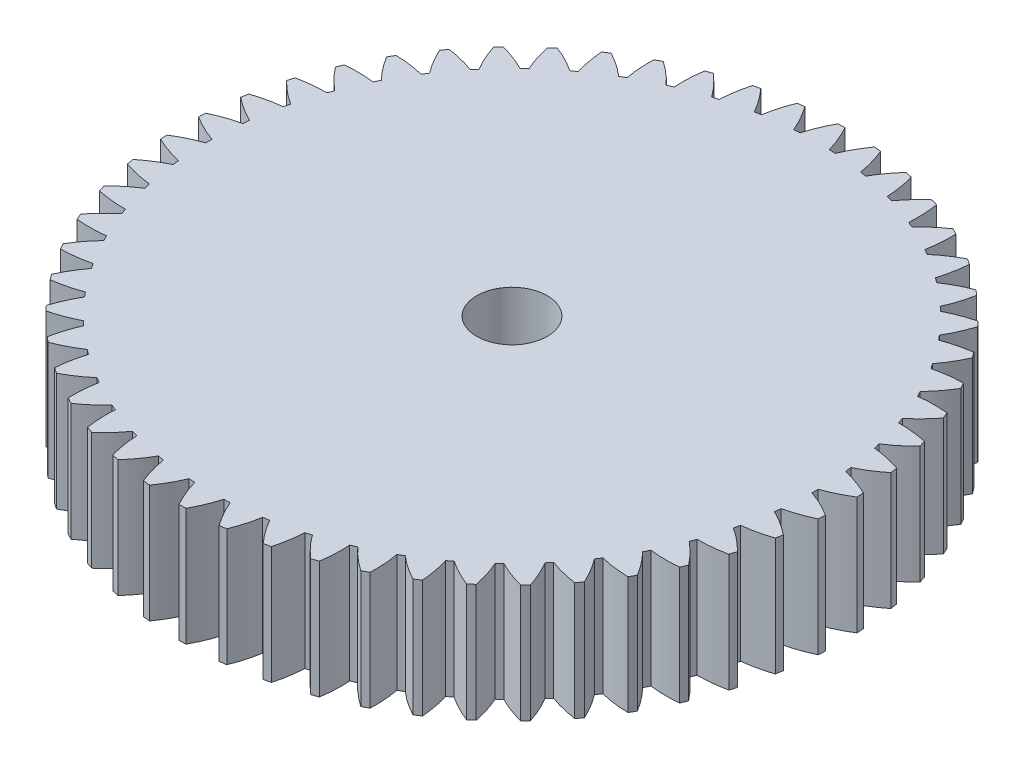
SolidWorks part; units mm, degrees
material "Custom Plastic"
ref_plane "Ön Düzlem" through (0, 0, 0) normal (0, 0, 1) x (1, 0, 0)
ref_plane "Üst Düzlem" through (0, 0, 0) normal (0, 1, 0) x (1, 0, 0)
ref_plane "Sağ Düzlem" through (0, 0, 0) normal (1, 0, 0) x (0, 0, -1)
sketch "Çizim2" plane through (0, 0, 0) normal (0, 1, 0) x (1, 0, 0)
  circle A0 centre (0, 0) radius 28
  dimension "D1" = 56
extrude "Yükseklik-Ekstrüzyon1" add sketch "Çizim2" along normal blind 10
sketch "Çizim3" plane through (0, 0, 0) normal (0, 1, 0) x (1, 0, 0)
  circle A0 centre (0, 0) radius 27
  circle A1 centre (0, 0) radius 28
  circle A2 centre (0, 0) radius 27
  circle A3 centre (0, 0) radius 28
  circle A4 centre (0, 0) radius 25.75
  circle A5 centre (0, 0) radius 24.47
  spline S0 degree 4 poles (24.4703, -0.0217) (24.4759, -0.0216) (24.4916, -0.0213) (24.5212, -0.0197) (24.5696, -0.0161) (24.6312, -0.0098) (24.7107, 0.0002) (24.8043, 0.0145) (24.907, 0.0329) (25.0185, 0.0556) (25.1296, 0.0808) (25.2402, 0.1082) (25.3502, 0.1376) (25.4832, 0.1756) (25.6424, 0.2247) (25.8278, 0.2869) (26.0374, 0.3633) (26.2501, 0.4475) (26.4588, 0.5354) (26.6686, 0.63) (26.8711, 0.7258) (27.0803, 0.8312) (27.2729, 0.9316) (27.4876, 1.0506) (27.6604, 1.1486) (27.887, 1.2848) (28.0205, 1.3674) (28.1762, 1.4664) (28.245, 1.5117) (28.2874, 1.5395) knots 0 0 0 0 0 0.005377 0.015084 0.028532 0.04661 0.064855 0.092111 0.119476 0.146842 0.174209 0.201575 0.228941 0.256307 0.307035 0.361767 0.4165 0.471232 0.525964 0.580697 0.635429 0.690161 0.744894 0.799626 0.854358 0.909091 0.954545 1 1 1 1 1 construction
  spline S1 degree 4 poles (24.4703, -0.0217) (24.4759, -0.0216) (24.4916, -0.0213) (24.5212, -0.0197) (24.5696, -0.0161) (24.6312, -0.0098) (24.7107, 0.0002) (24.8043, 0.0145) (24.907, 0.0329) (25.0185, 0.0556) (25.1296, 0.0808) (25.2402, 0.1082) (25.3502, 0.1376) (25.4832, 0.1756) (25.6424, 0.2247) (25.8278, 0.2869) (26.0374, 0.3633) (26.2501, 0.4475) (26.4588, 0.5354) (26.6686, 0.63) (26.8711, 0.7258) (27.0803, 0.8312) (27.2729, 0.9316) (27.4876, 1.0506) (27.6604, 1.1486) (27.8379, 1.2553) (27.9241, 1.308) (27.9681, 1.3353) knots 0 0 0 0 0 0.005377 0.015084 0.028532 0.04661 0.064855 0.092111 0.119476 0.146842 0.174209 0.201575 0.228941 0.256307 0.307035 0.361767 0.4165 0.471232 0.525964 0.580697 0.635429 0.690161 0.744894 0.799626 0.854358 0.909091 0.909091 0.909091 0.909091 0.909091
  spline S2 degree 4 poles (24.4703, 0.0217) (24.4759, 0.0216) (24.4916, 0.0213) (24.5212, 0.0197) (24.5696, 0.0161) (24.6312, 0.0098) (24.7107, -0.0002) (24.8043, -0.0145) (24.907, -0.0329) (25.0185, -0.0556) (25.1296, -0.0808) (25.2402, -0.1082) (25.3502, -0.1376) (25.4832, -0.1756) (25.6424, -0.2247) (25.8278, -0.2869) (26.0374, -0.3633) (26.2501, -0.4475) (26.4588, -0.5354) (26.6686, -0.63) (26.8711, -0.7258) (27.0803, -0.8312) (27.2729, -0.9316) (27.4876, -1.0506) (27.6604, -1.1486) (27.887, -1.2848) (28.0205, -1.3674) (28.1762, -1.4664) (28.245, -1.5117) (28.2874, -1.5395) knots 0 0 0 0 0 0.005377 0.015084 0.028532 0.04661 0.064855 0.092111 0.119476 0.146842 0.174209 0.201575 0.228941 0.256307 0.307035 0.361767 0.4165 0.471232 0.525964 0.580697 0.635429 0.690161 0.744894 0.799626 0.854358 0.909091 0.954545 1 1 1 1 1 construction
  spline S3 degree 4 poles (24.4703, 0.0217) (24.4759, 0.0216) (24.4916, 0.0213) (24.5212, 0.0197) (24.5696, 0.0161) (24.6312, 0.0098) (24.7107, -0.0002) (24.8043, -0.0145) (24.907, -0.0329) (25.0185, -0.0556) (25.1296, -0.0808) (25.2402, -0.1082) (25.3502, -0.1376) (25.4832, -0.1756) (25.6424, -0.2247) (25.8278, -0.2869) (26.0374, -0.3633) (26.2501, -0.4475) (26.4588, -0.5354) (26.6686, -0.63) (26.8711, -0.7258) (27.0803, -0.8312) (27.2729, -0.9316) (27.4876, -1.0506) (27.6604, -1.1486) (27.8379, -1.2553) (27.9241, -1.308) (27.9681, -1.3353) knots 0 0 0 0 0 0.005377 0.015084 0.028532 0.04661 0.064855 0.092111 0.119476 0.146842 0.174209 0.201575 0.228941 0.256307 0.307035 0.361767 0.4165 0.471232 0.525964 0.580697 0.635429 0.690161 0.744894 0.799626 0.854358 0.909091 0.909091 0.909091 0.909091 0.909091
  dimension "D1" = 56
  dimension "D2" = 54
  dimension "D3" = 48.94
  dimension "D4" = 51.5
extrude "Kes-Ekstrüzyon3" cut sketch "Çizim3" along normal blind 10 contours A2 S3 A3 S1 | A4 S3 A2 S1
pattern_circular "Dairesel Kaplama2" count 54 over 360 about axis through (0, 10, 0) along (0, 1, 0) of "Kes-Ekstrüzyon3"
sketch "Çizim4" plane through (0, 10, 0) normal (0, 1, 0) x (1, 0, 0)
  circle A0 centre (0, 0) radius 3
  dimension "D1" = 6
extrude "Kes-Ekstrüzyon4" cut sketch "Çizim4" against normal blind 10 contours A0
equation "\"DiametralPitch\"= 1"
equation "\"NumTeeth\"= 54"
equation "\"PressureAngle\"= 25"
equation "\"Thick\"= 10"
equation "\"HelixAngle\"= 45"
equation "\"Addendum\"= 1 / \"DiametralPitch\""
equation "\"Dedendum\"= 1.25 / \"DiametralPitch\""
equation "\"WorkingDepth\"= 2 / \"DiametralPitch\""
equation "\"WholeDepth\"= 2.25 / \"DiametralPitch\""
equation "\"Clearance\"= 0.25 / \"DiametralPitch\""
equation "\"ToothThickness\"= 1.5708 / \"DiametralPitch\""
equation "\"CircularPitch\"= pi / \"DiametralPitch\""
equation "\"PitchCircle\"= \"NumTeeth\" / \"DiametralPitch\""
equation "\"OutsideDiameter\"= ( \"NumTeeth\" + 2 ) / \"DiametralPitch\""
equation "\"Fillet\"= \"Clearance\" * cos ( \"PressureAngle\" ) * tan ( ( 90 + \"PressureAngle\" ) / 2 )"
equation "\"AddendumCircle\"= \"PitchCircle\" + ( 2 * \"Addendum\" )"
equation "\"DedendumCircle\"= \"PitchCircle\" - ( 2 * \"Dedendum\" )"
equation "\"BaseCircle\"= \"PitchCircle\" * cos ( \"PressureAngle\" )"
equation "\"PitchAngle\"= 360deg / \"NumTeeth\""
equation "\"Alpha\"= sqr ( \"PitchCircle\" ^ 2 - \"BaseCircle\" ^ 2 ) / \"BaseCircle\" * 180 / PI - \"PressureAngle\""
equation "\"Beta\"= ( \"PitchAngle\" / 4 - \"Alpha\" )"
equation "\"Phi\"= sqr ( ( \"AddendumCircle\" / 2 ) ^ 2 - ( \"BaseCircle\" / 2 ) ^ 2 ) / ( \"BaseCircle\" / 2 )"
equation "\"TwistAngle\"= (360 * \"Thick\" * tan (\"HelixAngle\")) / (\"DiametralPitch\" * \"NumTeeth\" * PI)"
equation "\"D1@Çizim2\"=\"OutsideDiameter\""
equation "\"D1@Yükseklik-Ekstrüzyon1\"=\"Thick\""
